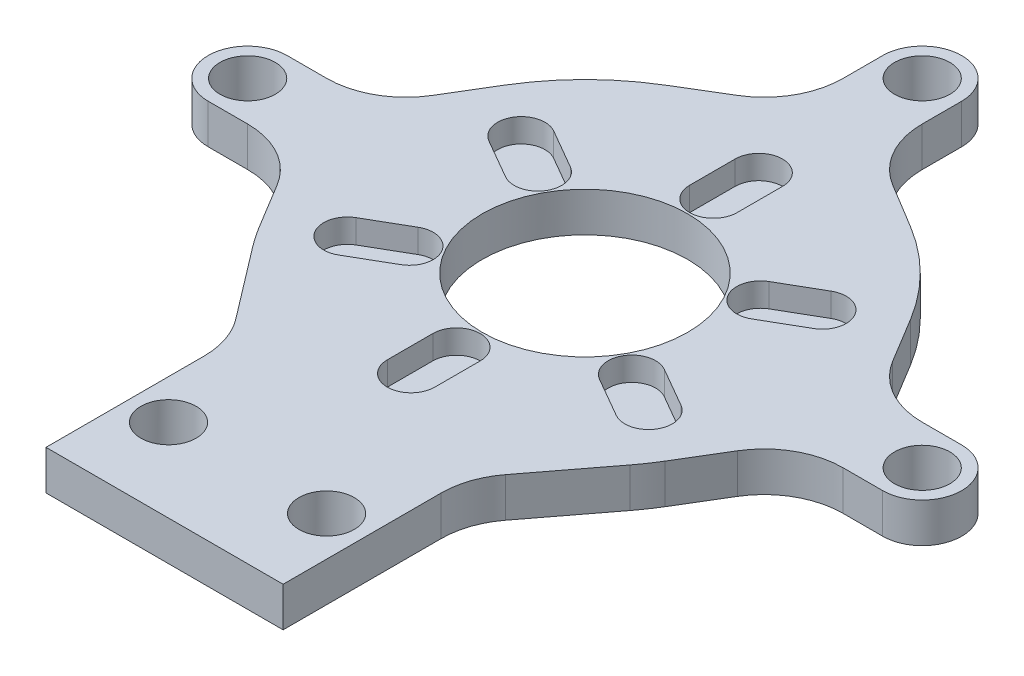
SolidWorks part; units mm, degrees
ref_plane "Front Plane" through (0, 0, 0) normal (0, 0, 1) x (1, 0, 0)
ref_plane "Top Plane" through (0, 0, 0) normal (0, 1, 0) x (1, 0, 0)
ref_plane "Right Plane" through (0, 0, 0) normal (1, 0, 0) x (0, 0, -1)
sketch "Esquisse1" plane through (0, 0, 0) normal (0, 1, 0) x (1, 0, 0)
  line L0 (-3, 16.25) -> (-3, 22)
  line L1 (3, 22) -> (3, 16.25)
  line L2 (0, -55) -> (0, 55) construction
  line L3 (12.5729, 10.7231) -> (17.5526, 13.5981)
  line L4 (20.5526, 8.4019) -> (15.5729, 5.5269)
  line L5 (15.5729, -5.5269) -> (20.5526, -8.4019)
  line L6 (17.5526, -13.5981) -> (12.5729, -10.7231)
  line L7 (3, -16.25) -> (3, -22)
  line L8 (-3, -22) -> (-3, -16.25)
  line L9 (-12.5729, -10.7231) -> (-17.5526, -13.5981)
  line L10 (-20.5526, -8.4019) -> (-15.5729, -5.5269)
  line L11 (-15.5729, 5.5269) -> (-20.5526, 8.4019)
  line L12 (-17.5526, 13.5981) -> (-12.5729, 10.7231)
  line L13 (0, 25) -> (6.5383, 25) construction
  line L14 (0, 30) -> (6.5383, 30) construction
  circle A0 centre (0, 0) radius 30
  circle A1 centre (0, 0) radius 13
  arc A2 (-3, 16.25) -> (3, 16.25) centre (0, 16.25) ccw
  arc A3 (3, 22) -> (-3, 22) centre (0, 22) ccw
  arc A4 (20.5526, 8.4019) -> (17.5526, 13.5981) centre (19.0526, 11) ccw
  arc A5 (12.5729, 10.7231) -> (15.5729, 5.5269) centre (14.0729, 8.125) ccw
  arc A6 (17.5526, -13.5981) -> (20.5526, -8.4019) centre (19.0526, -11) ccw
  arc A7 (15.5729, -5.5269) -> (12.5729, -10.7231) centre (14.0729, -8.125) ccw
  arc A8 (-3, -22) -> (3, -22) centre (0, -22) ccw
  arc A9 (3, -16.25) -> (-3, -16.25) centre (0, -16.25) ccw
  arc A10 (-20.5526, -8.4019) -> (-17.5526, -13.5981) centre (-19.0526, -11) ccw
  arc A11 (-12.5729, -10.7231) -> (-15.5729, -5.5269) centre (-14.0729, -8.125) ccw
  arc A12 (-17.5526, 13.5981) -> (-20.5526, 8.4019) centre (-19.0526, 11) ccw
  arc A13 (-15.5729, 5.5269) -> (-12.5729, 10.7231) centre (-14.0729, 8.125) ccw
  point P45 (0, 0)
  dimension "D1" = 60
  dimension "D2" = 26
  dimension "D4" = 3
  dimension "D5" = 5
  dimension "D3" = 5.75
  dimension "D6" = 6
extrude "Boss.-Extru.1" add sketch "Esquisse1" along normal blind 3
sketch "Esquisse2" plane through (0, 0, 0) normal (0, -1, 0) x (1, 0, 0)
  circle A0 centre (0, 0) radius 30
  circle A1 centre (0, 0) radius 30 construction
  circle A2 centre (0, 0) radius 13
  circle A3 centre (0, 0) radius 13 construction
extrude "Boss.-Extru.2" add sketch "Esquisse2" along normal blind 2
sketch "Esquisse3" plane through (0, 3, 0) normal (0, 1, 0) x (1, 0, 0)
  line L0 (-15, -33.1859) -> (-15, -53.1859)
  line L1 (-15, -53.1859) -> (15, -53.1859)
  line L2 (15, -53.1859) -> (15, -33.1859)
  line L3 (0, 0) -> (0, -49.6378) construction
  line L4 (-23.8595, -18.1859) -> (-17.0468, -27.1239)
  line L5 (23.8595, -18.1859) -> (17.0468, -27.1239)
  line L6 (-10, -46.1859) -> (10, -46.1859) construction
  line L7 (37.6732, 5) -> (42.6732, 5)
  line L9 (42.6732, -5) -> (37.6732, -5)
  line L10 (0, 0) -> (57.2295, 0) construction
  line L11 (25.6732, -15.5205) -> (29.1155, -9.8265)
  line L12 (25.6732, 15.5205) -> (29.1155, 9.8265)
  line L13 (-5, 37.6732) -> (-5, 42.6732)
  line L14 (5, 42.6732) -> (5, 37.6732)
  line L15 (15.5205, 25.6732) -> (9.8265, 29.1155)
  line L16 (-15.5205, 25.6732) -> (-9.8265, 29.1155)
  line L17 (-37.6732, -5) -> (-42.6732, -5)
  line L18 (-42.6732, 5) -> (-37.6732, 5)
  line L19 (-25.6732, 15.5205) -> (-29.1155, 9.8265)
  line L20 (-25.6732, -15.5205) -> (-29.1155, -9.8265)
  circle A0 centre (0, 0) radius 30 construction
  arc A2 (-15, -33.1859) -> (-17.0468, -27.1239) centre (-25, -33.1859) ccw
  arc A3 (15, -33.1859) -> (17.0468, -27.1239) centre (25, -33.1859) cw
  arc A4 (-23.8595, -18.1859) -> (23.8595, -18.1859) centre (0, 0) ccw
  circle A5 centre (-10, -42.6859) radius 3.5
  circle A6 centre (10, -42.6859) radius 3.5
  arc A7 (37.6732, 5) -> (29.1155, 9.8265) centre (37.6732, 15) cw
  arc A8 (37.6732, -5) -> (29.1155, -9.8265) centre (37.6732, -15) ccw
  arc A9 (42.6732, -5) -> (42.6732, 5) centre (42.6732, 0) ccw
  arc A10 (25.6732, 15.5205) -> (25.6732, -15.5205) centre (0, 0) cw
  arc A11 (-5, 37.6732) -> (-9.8265, 29.1155) centre (-15, 37.6732) cw
  arc A12 (5, 37.6732) -> (9.8265, 29.1155) centre (15, 37.6732) ccw
  arc A13 (5, 42.6732) -> (-5, 42.6732) centre (0, 42.6732) ccw
  arc A14 (-15.5205, 25.6732) -> (15.5205, 25.6732) centre (0, 0) cw
  arc A15 (-37.6732, -5) -> (-29.1155, -9.8265) centre (-37.6732, -15) cw
  arc A16 (-37.6732, 5) -> (-29.1155, 9.8265) centre (-37.6732, 15) ccw
  arc A17 (-42.6732, 5) -> (-42.6732, -5) centre (-42.6732, 0) ccw
  arc A18 (-25.6732, -15.5205) -> (-25.6732, 15.5205) centre (0, 0) cw
  point P59 (0, 0)
  dimension "D1" = 10
  dimension "D2" = 10
  dimension "D4" = 20
  dimension "D6" = 7
  dimension "D8" = 20
  dimension "D10" = 10
  dimension "D11" = 10
  dimension "D13" = 12
  dimension "D14" = 3
  dimension "D3" = 30
  dimension "D5" = 15
  dimension "D7" = 7
  dimension "D9" = 10
  dimension "D12" = 5
extrude "Boss.-Extru.3" add sketch "Esquisse3" against normal up to surface (5 mm away) up to face at (0, -2, -30)
sketch "Esquisse4" plane through (0, 3, 0) normal (0, 1, 0) x (1, 0, 0)
  circle A0 centre (-42.6732, 0) radius 3.5
  circle A1 centre (42.6732, 0) radius 3.5
  arc A2 (-42.6732, 5) -> (-42.6732, -5) centre (-42.6732, 0) ccw construction
  circle A3 centre (0, 42.6732) radius 3.5
  point P2 (-40.8436, 0.9303)
  dimension "D1" = 7
extrude "Enlèv. mat.-Extru.1" cut sketch "Esquisse4" against normal through all
